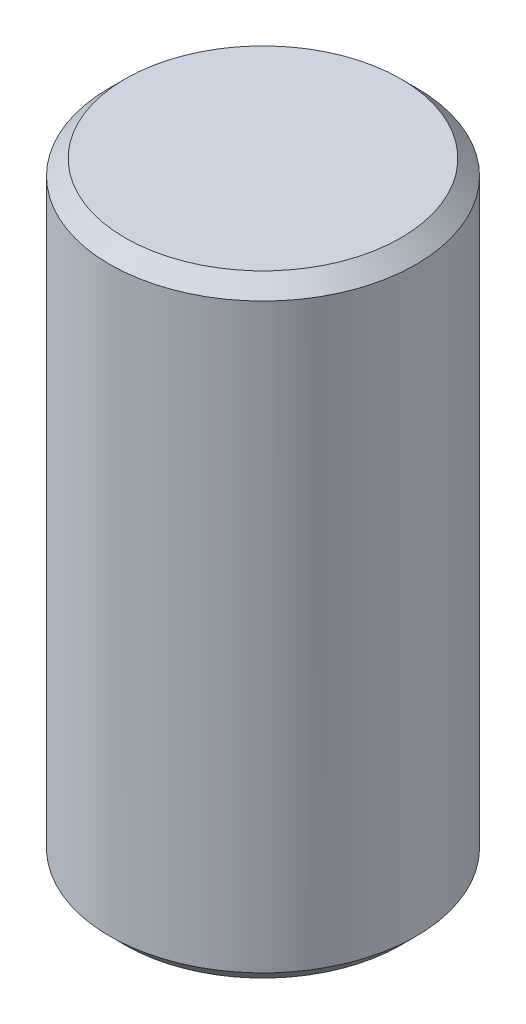
SolidWorks part; units mm, degrees
ref_plane "Ebene vorne" through (0, 0, 0) normal (0, 0, 1) x (1, 0, 0)
ref_plane "Ebene oben" through (0, 0, 0) normal (0, 1, 0) x (1, 0, 0)
ref_plane "Ebene rechts" through (0, 0, 0) normal (1, 0, 0) x (0, 0, -1)
sketch "Skizze1" plane through (0, 0, 0) normal (0, 0, 1) x (1, 0, 0)
  line L0 (0, 0) -> (0, 62.1508) construction
  line L2 (0, 0) -> (5, 0)
  line L3 (0, 0) -> (0, 20)
  line L4 (0, 20) -> (5, 20)
  line L15 (5, 20) -> (5, 0)
  dimension "D1" = 20
  dimension "D2" = 10
revolve "Rotation1" add sketch "Skizze1" angle 360 about L0
chamfer "Fase1" distance 0.5 angle 45 2 edges at (0, 0, -5) (0, 20, -5)
